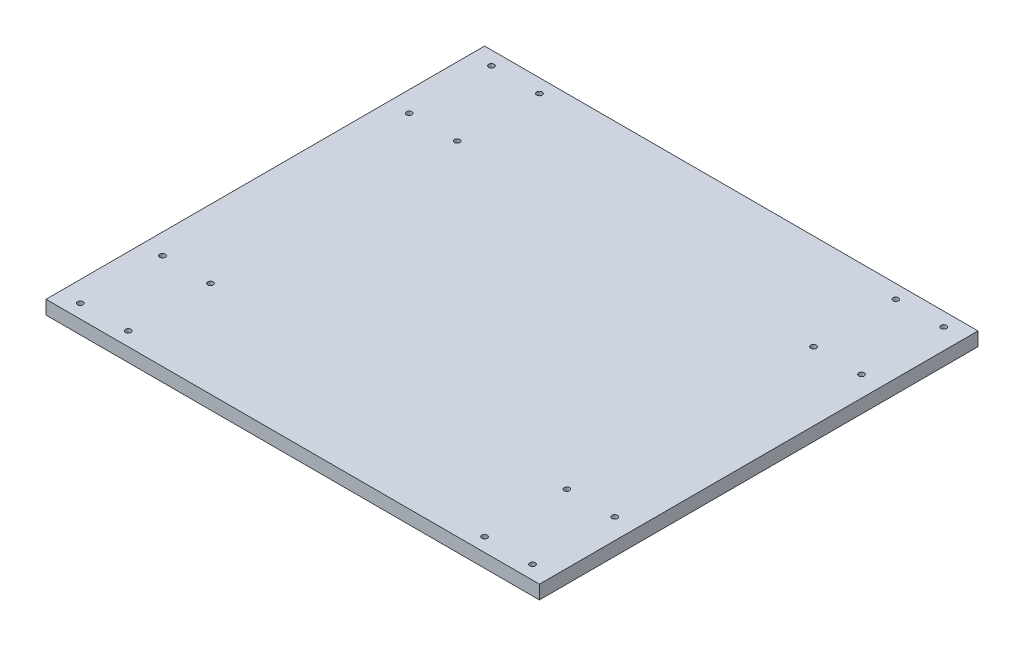
SolidWorks part; units mm, degrees
ref_plane "Front" through (0, 0, 0) normal (0, 0, 1) x (1, 0, 0)
ref_plane "Top" through (0, 0, 0) normal (0, 1, 0) x (1, 0, 0)
ref_plane "Right" through (0, 0, 0) normal (1, 0, 0) x (0, 0, -1)
sketch "Sketch1" plane through (0, 0, 0) normal (0, 1, 0) x (1, 0, 0)
  line L1 (-228.6, -203.2) -> (228.6, -203.2)
  line L2 (-228.6, -203.2) -> (-228.6, 203.2)
  line L3 (-228.6, 203.2) -> (228.6, 203.2)
  line L4 (228.6, -203.2) -> (228.6, 203.2)
  line L5 (-228.6, -203.2) -> (228.6, 203.2) construction
  line L6 (-228.6, 203.2) -> (228.6, -203.2) construction
  point P0 (0, 0)
  dimension "D1" = 457.2
  dimension "D2" = 406.4
extrude "Boss-Extrude1" add sketch "Sketch1" along normal blind 12.7 contours L3 L4 L1 L2
sketch "Sketch2" plane through (0, 12.7, 0) normal (0, 1, 0) x (1, 0, 0)
  line L0 (-228.6, -203.2) -> (228.6, -203.2) construction
  line L1 (-228.6, -203.2) -> (-228.6, 203.2) construction
  point P0 (-209.55, -190.5)
  point P1 (-209.55, -114.3)
  point P2 (-165.1, -114.3)
  point P3 (-165.1, -190.5)
  point P4 (0, 0)
  point P5 (0, 0)
  point P6 (0, 0)
  point P7 (0, 0)
  dimension "D1" = 44.45
  dimension "D2" = 76.2
  dimension "D3" = 12.7
  dimension "D4" = 19.05
hole_wizard "1/4-20 Tapped Hole1" positions "Sketch3" profile "Sketch4" tap size "1/4-20" standard "ANSI Inch"
sketch "Sketch3" plane through (0, 12.7, 0) normal (0, 1, 0) x (1, 0, 0)
  point P0 (-209.55, -190.5)
  point P3 (-209.55, -114.3)
  point P6 (-165.1, -114.3)
  point P9 (-165.1, -190.5)
sketch "Sketch4" plane through (-209.55, 12.7, 190.5) normal (1, 0, 0) x (0, 0, 1)
  line L0 (0, 0) -> (0, 18.0438)
  line L1 (0, 18.0438) -> (2.5527, 16.51)
  line L2 (2.5527, 16.51) -> (2.5527, 0)
  line L5 (2.5527, 0) -> (0, 0)
  line L10 (0, 18.0438) -> (-2.5527, 16.51) construction
  line L11 (0, -6.35) -> (0, 107.95) construction
  dimension "Tap Drill Dia." = 5.1054
  dimension "Tap Drill Depth" = 16.51
  dimension "Drill Angle" = 118
mirror "Mirror1" about plane through (0, 0, 0) normal (1, 0, 0) of "1/4-20 Tapped Hole1"
mirror "Mirror2" about plane through (0, 0, 0) normal (0, 0, 1) of "Mirror1", "1/4-20 Tapped Hole1"
